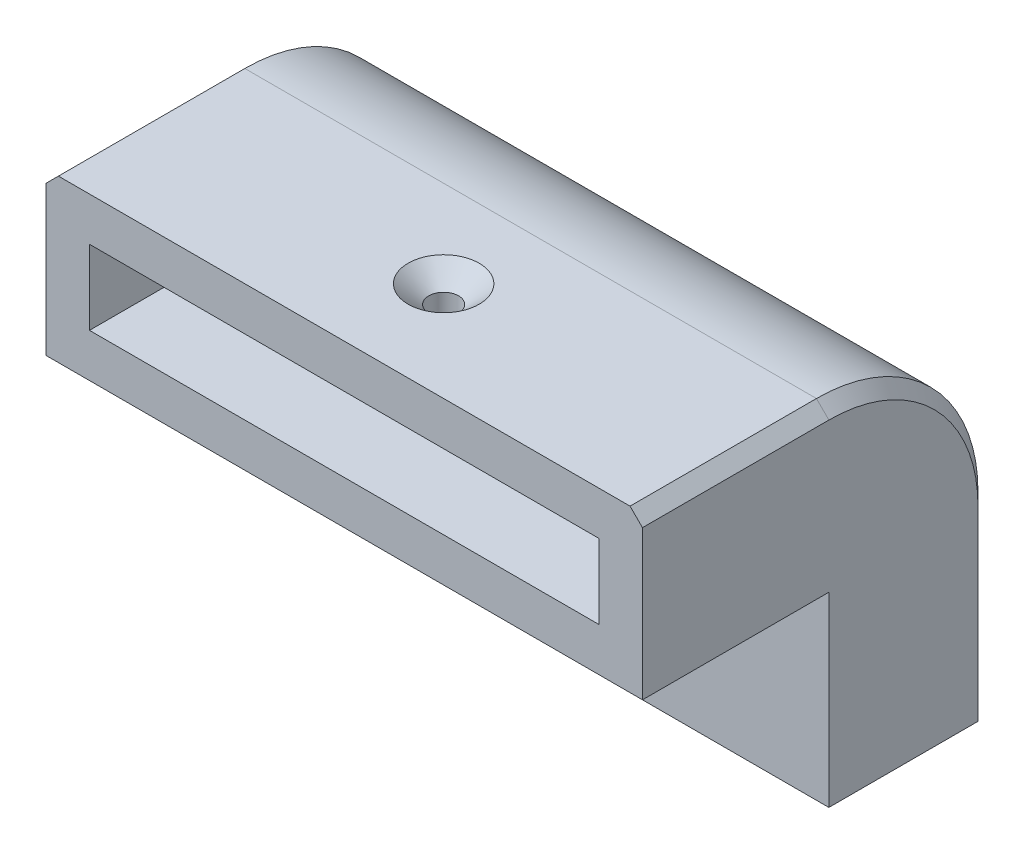
SolidWorks part; units mm, degrees
ref_plane "Front Plane" through (0, 0, 0) normal (0, 0, 1) x (1, 0, 0)
ref_plane "Top Plane" through (0, 0, 0) normal (0, 1, 0) x (1, 0, 0)
ref_plane "Right Plane" through (0, 0, 0) normal (1, 0, 0) x (0, 0, -1)
sketch "Sketch1" plane through (0, 0, 0) normal (0, 1, 0) x (1, 0, 0)
  line L0 (-30.48, 8.255) -> (30.48, 8.255)
  line L1 (-25.4, 3.175) -> (25.4, 3.175)
  line L2 (-25.4, 3.175) -> (-25.4, -3.175)
  line L3 (-25.4, -3.175) -> (25.4, -3.175)
  line L4 (25.4, 3.175) -> (25.4, -3.175)
  line L5 (-25.4, 3.175) -> (25.4, -3.175) construction
  line L6 (-25.4, -3.175) -> (25.4, 3.175) construction
  line L7 (30.48, 8.255) -> (30.48, -8.255)
  line L8 (-30.48, -8.255) -> (30.48, -8.255)
  line L9 (-30.48, 8.255) -> (-30.48, -8.255)
  point P0 (0, 0)
  dimension "D1" = 50.8
  dimension "D2" = 6.35
  dimension "D3" = 5.08
extrude "Boss-Extrude1" add sketch "Sketch1" along normal blind 19.05
sketch "Sketch5" plane through (30.48, 0, 0) normal (1, 0, 0) x (0, 0, -1)
  line L0 (-13.4061, 19.05) -> (12.4649, 19.05) construction
  line L2 (-8.255, 35.56) -> (-27.305, 35.56)
  line L3 (-27.305, 35.56) -> (-27.305, 19.05)
  line L4 (-8.255, 19.05) -> (-27.305, 19.05)
  line L5 (-8.255, 15.823) -> (-8.255, 19.05) construction
  line L6 (-8.255, 19.05) -> (-8.255, 0) construction
  line L7 (8.255, 19.05) -> (-8.255, 19.05)
  arc A0 (8.255, 19.05) -> (-8.255, 35.56) centre (-8.255, 19.05) ccw
extrude "Boss-Extrude2" add sketch "Sketch5" against normal up to surface (60.96 mm away) up to face at (-30.48, 9.525, 0)
sketch "Sketch6" plane through (0, 0, 27.305) normal (0, 0, 1) x (1, 0, 0)
  line L0 (0, 35.56) -> (0, 19.05) construction
  line L1 (-30.48, 35.56) -> (30.48, 35.56) construction
  line L2 (-30.48, 19.05) -> (30.48, 19.05) construction
  line L3 (-30.48, 27.305) -> (30.48, 27.305) construction
  line L4 (-30.48, 19.05) -> (-30.48, 35.56) construction
  line L5 (30.48, 35.56) -> (30.48, 19.05) construction
  line L7 (-25.4, 30.48) -> (25.4, 30.48)
  line L8 (-25.4, 30.48) -> (-25.4, 24.13)
  line L9 (-25.4, 24.13) -> (25.4, 24.13)
  line L10 (25.4, 30.48) -> (25.4, 24.13)
  line L11 (-25.4, 30.48) -> (25.4, 24.13) construction
  line L12 (-25.4, 24.13) -> (25.4, 30.48) construction
  point P12 (0, 27.305)
  dimension "D1" = 6.35
  dimension "D2" = 50.8
extrude "Cut-Extrude1" cut sketch "Sketch6" against normal blind 19.05
sketch "Sketch7" plane through (0, 0, -8.255) normal (0, 0, -1) x (-1, 0, 0)
  line L0 (-30.48, 0) -> (30.48, 0) construction
  circle A0 centre (0, 10.16) radius 1.524
  dimension "D1" = 10.16
  dimension "D2" = 3.048
extrude "Cut-Extrude2" cut sketch "Sketch7" against normal through all
sketch "Sketch8" plane through (0, 35.56, 0) normal (0, 1, 0) x (1, 0, 0)
  line L0 (-30.48, -27.305) -> (30.48, -27.305) construction
  circle A0 centre (0, -17.145) radius 1.524
  dimension "D1" = 10.16
  dimension "D2" = 3.048
extrude "Cut-Extrude3" cut sketch "Sketch8" against normal through all
chamfer "Chamfer1" distance 2.1082 angle 41 2 edges at (-1.524, 10.16, 8.255) (0, 35.56, 18.669)
sketch "Sketch9" plane through (0, 0, 27.305) normal (0, 0, 1) x (1, 0, 0)
  line L14 (26.035, 23.495) -> (26.035, 31.115)
  line L15 (-26.035, 23.495) -> (26.035, 23.495)
  line L16 (-26.035, 31.115) -> (-26.035, 23.495)
  line L17 (26.035, 31.115) -> (-26.035, 31.115)
  line L18 (26.035, 23.495) -> (26.035, 31.115)
  line L19 (-26.035, 23.495) -> (26.035, 23.495)
  line L20 (-26.035, 31.115) -> (-26.035, 23.495)
  line L21 (26.035, 31.115) -> (-26.035, 31.115)
  dimension "D1" = 0.635
extrude "Cut-Extrude4" cut sketch "Sketch9" against normal blind 19.05
sketch "Sketch10" plane through (0, 0, 0) normal (0, -1, 0) x (1, 0, 0)
  line L22 (26.035, -3.81) -> (26.035, 3.81)
  line L23 (-26.035, -3.81) -> (26.035, -3.81)
  line L24 (-26.035, 3.81) -> (-26.035, -3.81)
  line L25 (26.035, 3.81) -> (-26.035, 3.81)
  line L26 (26.035, -3.81) -> (26.035, 3.81)
  line L27 (-26.035, -3.81) -> (26.035, -3.81)
  line L28 (-26.035, 3.81) -> (-26.035, -3.81)
  line L29 (26.035, 3.81) -> (-26.035, 3.81)
  dimension "D1" = 0.635
extrude "Cut-Extrude5" cut sketch "Sketch10" against normal blind 19.05
chamfer "Chamfer2" distance 1.27 angle 45 6 edges at (30.48, 9.525, -8.255) (-30.48, 30.7243, -3.4193) (30.48, 30.7243, -3.4193) (-30.48, 35.56, 17.78) (30.48, 35.56, 17.78) (-30.48, 9.525, -8.255)
